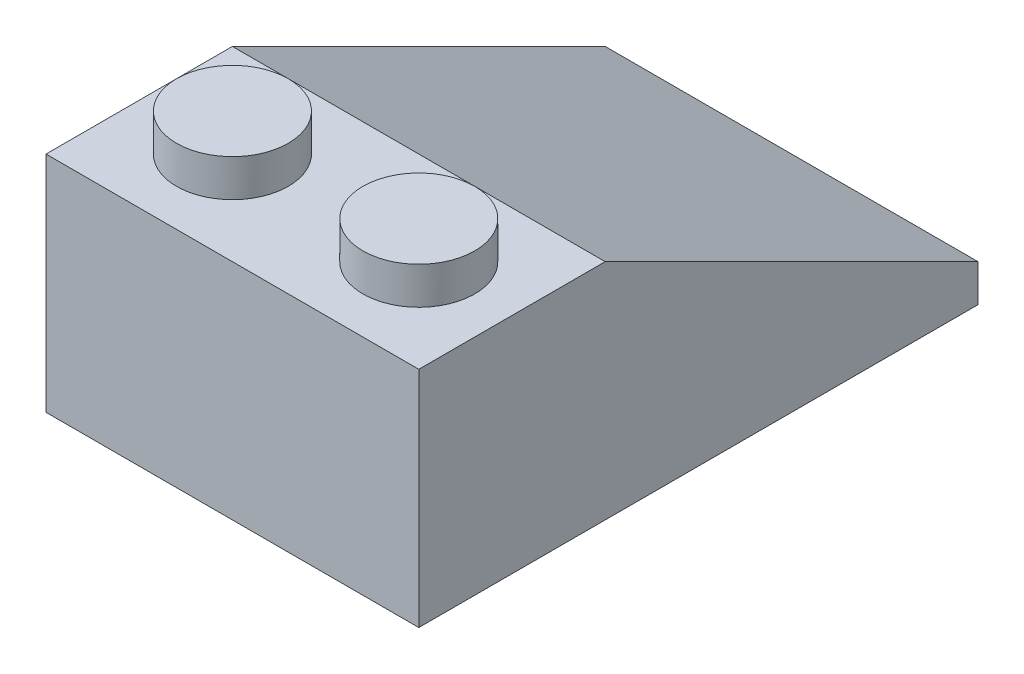
SolidWorks part; units mm, degrees
ref_plane "Front Plane" through (0, 0, 0) normal (0, 0, 1) x (1, 0, 0)
ref_plane "Top Plane" through (0, 0, 0) normal (0, 1, 0) x (1, 0, 0)
ref_plane "Right Plane" through (0, 0, 0) normal (1, 0, 0) x (0, 0, -1)
sketch "Sketch1" plane through (0, 0, 0) normal (1, 0, 0) x (0, 0, -1)
  line L0 (0, 0) -> (24, 0)
  line L3 (8, 9.6) -> (0, 9.6)
  line L4 (0, 9.6) -> (0, 0)
  line L5 (24, 0) -> (24, 1.6)
  line L6 (24, 1.6) -> (8, 9.6)
  dimension "D1" = 9.6
  dimension "D2" = 24
  dimension "D3" = 8
  dimension "D4" = 1.6
extrude "Boss-Extrude1" add sketch "Sketch1" along normal blind 16
sketch "Sketch2" plane through (0, 9.6, 0) normal (0, 1, 0) x (1, 0, 0)
  line L0 (0, 4) -> (4, 4) construction
  line L1 (0, 8) -> (0, 0) construction
  line L2 (4, 4) -> (12, 4) construction
  circle A0 centre (4, 4) radius 2.4
  circle A2 centre (12, 4) radius 2.4
  dimension "D1" = 4.8
  dimension "D4" = 4.8
  dimension "D2" = 4
  dimension "D3" = 8
extrude "Boss-Extrude2" add sketch "Sketch2" along normal blind 1.6
shell "Shell1" thickness 1.6
